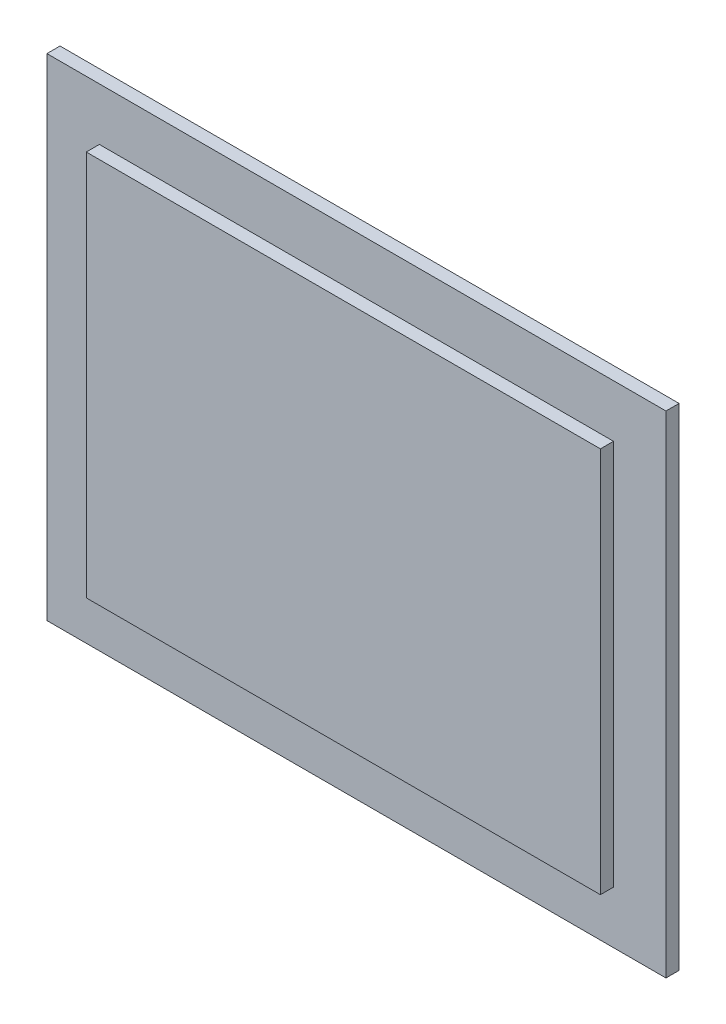
SolidWorks part; units mm, degrees
ref_plane "Front Plane" through (0, 0, 0) normal (0, 0, 1) x (1, 0, 0)
ref_plane "Top Plane" through (0, 0, 0) normal (0, 1, 0) x (1, 0, 0)
ref_plane "Right Plane" through (0, 0, 0) normal (1, 0, 0) x (0, 0, -1)
sketch "Sketch1" plane through (0, 0, 0) normal (0, 0, 1) x (1, 0, 0)
  line L1 (0, 0) -> (74.93, 0)
  line L2 (0, 0) -> (0, 59.436)
  line L3 (0, 59.436) -> (74.93, 59.436)
  line L4 (74.93, 0) -> (74.93, 59.436)
  dimension "D1" = 74.93
  dimension "D2" = 59.436
extrude "Extrude1" add sketch "Sketch1" against normal blind 1.5875
sketch "Sketch2" plane through (0, 0, 0) normal (0, 0, 1) x (1, 0, 0)
  line L0 (0, 0) -> (6.35, 0) construction
  line L1 (0, 0) -> (74.93, 0) construction
  line L2 (6.35, 0) -> (6.35, 6.35) construction
  line L3 (74.93, 59.436) -> (68.58, 59.436) construction
  line L4 (74.93, 59.436) -> (0, 59.436) construction
  line L5 (68.58, 59.436) -> (68.58, 53.086) construction
  line L6 (74.93, 0) -> (74.93, 59.436) construction
  line L7 (6.35, 6.35) -> (68.58, 6.35)
  line L8 (6.35, 6.35) -> (6.35, 53.086)
  line L9 (6.35, 53.086) -> (68.58, 53.086)
  line L10 (68.58, 6.35) -> (68.58, 53.086)
  point P16 (6.35, 1.5626)
  dimension "D1" = 6.35
  dimension "D2" = 62.23
  dimension "D3" = 6.35
  dimension "D4" = 46.736
extrude "Extrude2" add sketch "Sketch2" along normal blind 1.5875
